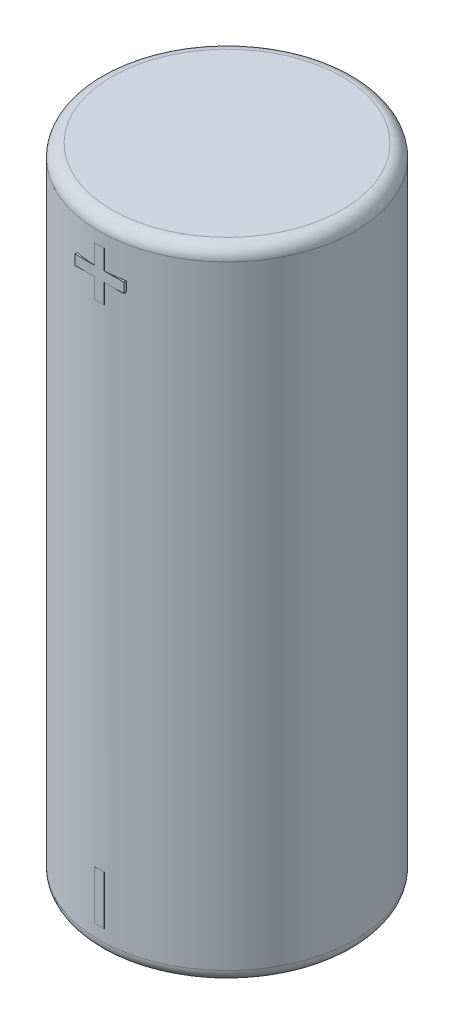
SolidWorks part; units mm, degrees
ref_plane "Front Plane" through (0, 0, 0) normal (0, 0, 1) x (1, 0, 0)
ref_plane "Top Plane" through (0, 0, 0) normal (0, 1, 0) x (1, 0, 0)
ref_plane "Right Plane" through (0, 0, 0) normal (1, 0, 0) x (0, 0, -1)
sketch "Sketch1" plane through (0, 0, 0) normal (0, 1, 0) x (1, 0, 0)
  circle A0 centre (0, 0) radius 13
  dimension "D1" = 26
extrude "Boss-Extrude1" add sketch "Sketch1" along normal blind 65
fillet "Fillet1" radius 1.27 1 edges at (0, 65, 13)
fillet "Fillet2" radius 1.27 1 edges at (0, 0, 13)
ref_plane "Plane1" through (0, 0, 13) normal (0, 0, 1) x (1, 0, 0)
sketch "Sketch2" plane through (0, 0, 13) normal (0, 0, 1) x (1, 0, 0)
  line L0 (11.73, 65) -> (-11.73, 65) construction
  line L1 (11.73, 65) -> (-11.73, 65)
  line L2 (0, 65) -> (0, 0) construction
  line L4 (-0.5, 62.5) -> (0.5, 62.5)
  line L5 (-0.5, 62.5) -> (-0.5, 57.5)
  line L6 (-0.5, 57.5) -> (0.5, 57.5)
  line L7 (0.5, 62.5) -> (0.5, 57.5)
  line L8 (-2.5, 60.5) -> (2.5, 60.5)
  line L9 (-2.5, 60.5) -> (-2.5, 59.5)
  line L10 (-2.5, 59.5) -> (2.5, 59.5)
  line L11 (2.5, 60.5) -> (2.5, 59.5)
  line L12 (-0.5, 7.5) -> (0.5, 7.5)
  line L13 (-0.5, 7.5) -> (-0.5, 2.5)
  line L14 (-0.5, 2.5) -> (0.5, 2.5)
  line L15 (0.5, 7.5) -> (0.5, 2.5)
  point P13 (0, 60)
  point P18 (0, 5)
  dimension "D1" = 5
  dimension "D2" = 5
  dimension "D3" = 1
  dimension "D4" = 1
  dimension "D5" = 0.5
  dimension "D6" = 2.5
  dimension "D7" = 5
  dimension "D8" = 0.5
  dimension "D9" = 2.5
  dimension "D10" = 1
  dimension "D11" = 5
  dimension "D12" = 5
  dimension "D13" = 2.5
  dimension "D14" = 0.5
extrude "Boss-Extrude2" add sketch "Sketch2" against normal blind 10 contours L2 L12 L13 L14 | L12 L2 L14 L15 | L5 L6 L7 L4 | L8 L11 L10 L9
sketch "Sketch3" plane through (0, 65, 0) normal (0, 1, 0) x (1, 0, 0)
  point P0 (0, 0)
sketch "Sketch4" plane through (0, 0, 0) normal (0, -1, 0) x (-1, 0, 0)
  point P0 (0, 0)
